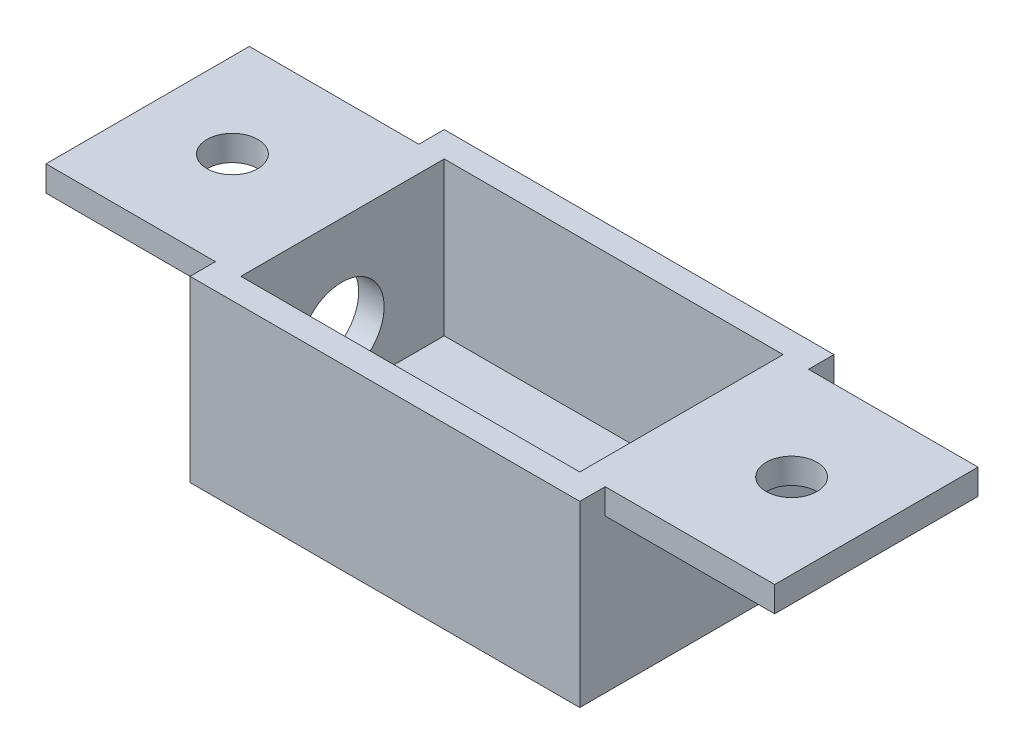
SolidWorks part; units mm, degrees
ref_plane "前视基准面" through (0, 0, 0) normal (0, 0, 1) x (1, 0, 0)
ref_plane "上视基准面" through (0, 0, 0) normal (0, 1, 0) x (1, 0, 0)
ref_plane "右视基准面" through (0, 0, 0) normal (1, 0, 0) x (0, 0, -1)
sketch "草图1" plane through (0, 0, 0) normal (0, 0, 1) x (1, 0, 0)
  line L0 (-66, 28.8935) -> (-43, 28.8935)
  line L1 (-43, 28.8935) -> (-43, 10.812)
  line L2 (-43, 10.812) -> (-3, 10.812)
  line L3 (-3, 10.812) -> (-3, 28.8935)
  line L4 (-3, 28.8935) -> (20, 28.8935)
  line L5 (-66, 28.8935) -> (-66, 25.8935)
  line L6 (-66, 25.8935) -> (-46, 25.8935)
  line L7 (-46, 25.8935) -> (-46, 7.812)
  line L8 (-46, 7.812) -> (0, 7.812)
  line L9 (0, 7.812) -> (0, 25.8935)
  line L10 (0, 25.8935) -> (20, 25.8935)
  line L11 (20, 25.8935) -> (20, 28.8935)
  dimension "D1" = 3
  dimension "D2" = 3
  dimension "D3" = 3
  dimension "D4" = 3
  dimension "D5" = 3
  dimension "D6" = 20
  dimension "D7" = 20
  dimension "D8" = 40
extrude "凸台-拉伸1" add sketch "草图1" along normal blind 24
sketch "草图2" plane through (0, 0, 24) normal (0, 0, 1) x (1, 0, 0)
  line L1 (20, 28.8935) -> (-3, 28.8935) construction
  line L2 (-46, 7.812) -> (0, 7.812)
  line L3 (-46, 7.812) -> (-46, 28.8935)
  line L4 (-46, 28.8935) -> (0, 28.8935)
  line L5 (0, 7.812) -> (0, 28.8935)
extrude "凸台-拉伸2" add sketch "草图2" along normal blind 3
sketch "草图3" plane through (0, 0, 0) normal (0, 0, -1) x (-1, 0, 0)
  line L0 (43, 28.8935) -> (66, 28.8935) construction
  line L1 (0, 7.812) -> (46, 7.812)
  line L2 (0, 7.812) -> (0, 28.8935)
  line L3 (0, 28.8935) -> (46, 28.8935)
  line L4 (46, 7.812) -> (46, 28.8935)
extrude "凸台-拉伸3" add sketch "草图3" along normal blind 3
sketch "草图6" plane through (-46, 0, 0) normal (-1, 0, 0) x (0, 0, 1)
  circle A0 centre (12.0936, 17.3392) radius 5
  dimension "D1" = 10
extrude "切除-拉伸2" cut sketch "草图6" against normal blind 10
sketch "草图7" plane through (0, 25.8935, 0) normal (0, -1, 0) x (1, 0, 0)
  line L0 (-46, 27) -> (-46, -3) construction
  line L1 (0, 27) -> (0, -3) construction
  circle A0 centre (10, 12) radius 3
  circle A1 centre (-56, 12) radius 3
  dimension "D1" = 6
  dimension "D2" = 6
  dimension "D3" = 10
  dimension "D4" = 10
extrude "切除-拉伸3" cut sketch "草图7" against normal blind 10
